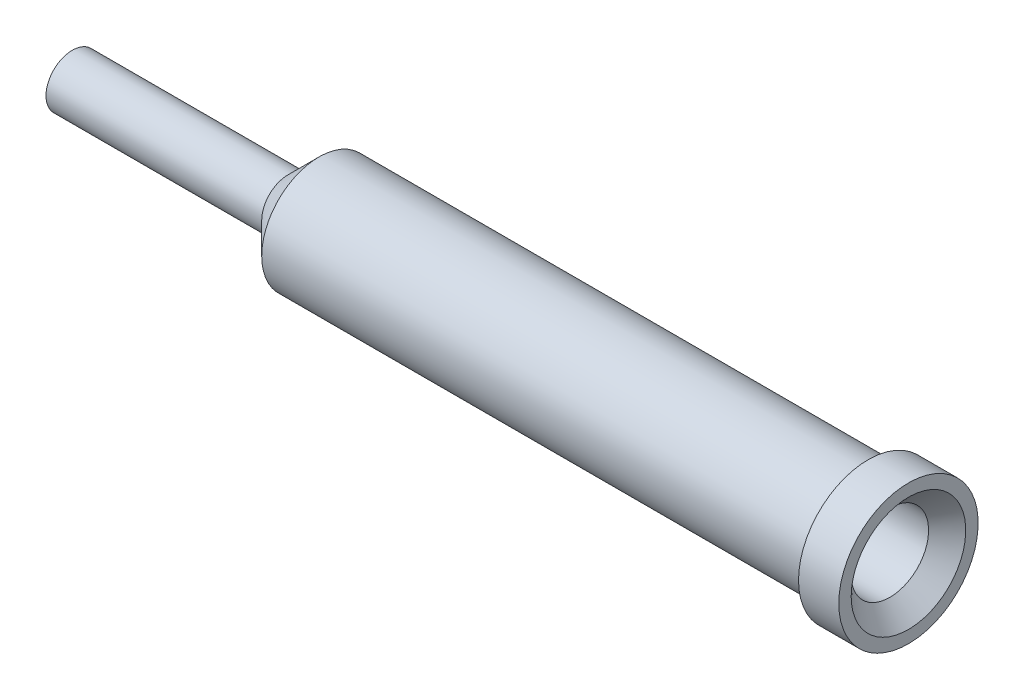
SolidWorks part; units mm, degrees
ref_plane "Front" through (0, 0, 0) normal (0, 0, 1) x (1, 0, 0)
ref_plane "Top" through (0, 0, 0) normal (0, 1, 0) x (1, 0, 0)
ref_plane "Right" through (0, 0, 0) normal (1, 0, 0) x (0, 0, -1)
sketch "Sketch1" plane through (0, 0, 0) normal (0, 1, 0) x (1, 0, 0)
  line L0 (-52.1171, 0) -> (59.7697, 0) construction
  line L1 (-27, 0.85) -> (-20.0343, 0.85)
  line L2 (-27, 1.25) -> (-20.2, 1.25) construction
  line L3 (-20.2, 1.25) -> (-19.2, 2.25) construction
  line L4 (-19.2, 2.25) -> (-1.7, 2.25) construction
  line L5 (-1.7, 2.25) -> (-1.7, 2.65) construction
  line L6 (-1.7, 2.65) -> (0, 2.65) construction
  line L7 (-20.0343, 0.85) -> (-19.0343, 1.85)
  line L8 (-19.0343, 1.85) -> (-1.3, 1.85)
  line L9 (-1.3, 1.85) -> (-1.3, 2.25)
  line L10 (-1.3, 2.25) -> (0, 2.25)
  line L11 (-27, 1.25) -> (-27, 0.85) construction
  line L12 (0, 2.65) -> (0, 2.25) construction
  line L13 (0, 2.25) -> (0, 1.85)
  line L14 (0, 1.85) -> (-0.6, 1.25)
  line L15 (-0.6, 1.25) -> (-8.2783, 1.25)
  line L16 (-8.2783, 1.25) -> (-9, 0)
  line L17 (-27, 0.85) -> (-27, 0.45)
  line L18 (-27, 0.45) -> (-26, 0.45)
  line L19 (-26, 0.45) -> (-26, 0)
  line L20 (-9, 0) -> (-26, 0)
  dimension "D1" = 0.4
  dimension "D2" = 1.7
  dimension "D3" = 2.25
  dimension "D4" = 1.25
  dimension "D5" = 17.5
  dimension "D6" = 45
  dimension "D7" = 2.65
  dimension "D8" = 27
  dimension "D9" = 2.5
  dimension "D10" = 45
  dimension "D11" = 60
  dimension "D12" = 9
  dimension "D13" = 0.4
  dimension "D14" = 1
  dimension "D15" = 0.4
revolve "Revolve2" add sketch "Sketch1" angle 360 about L0
